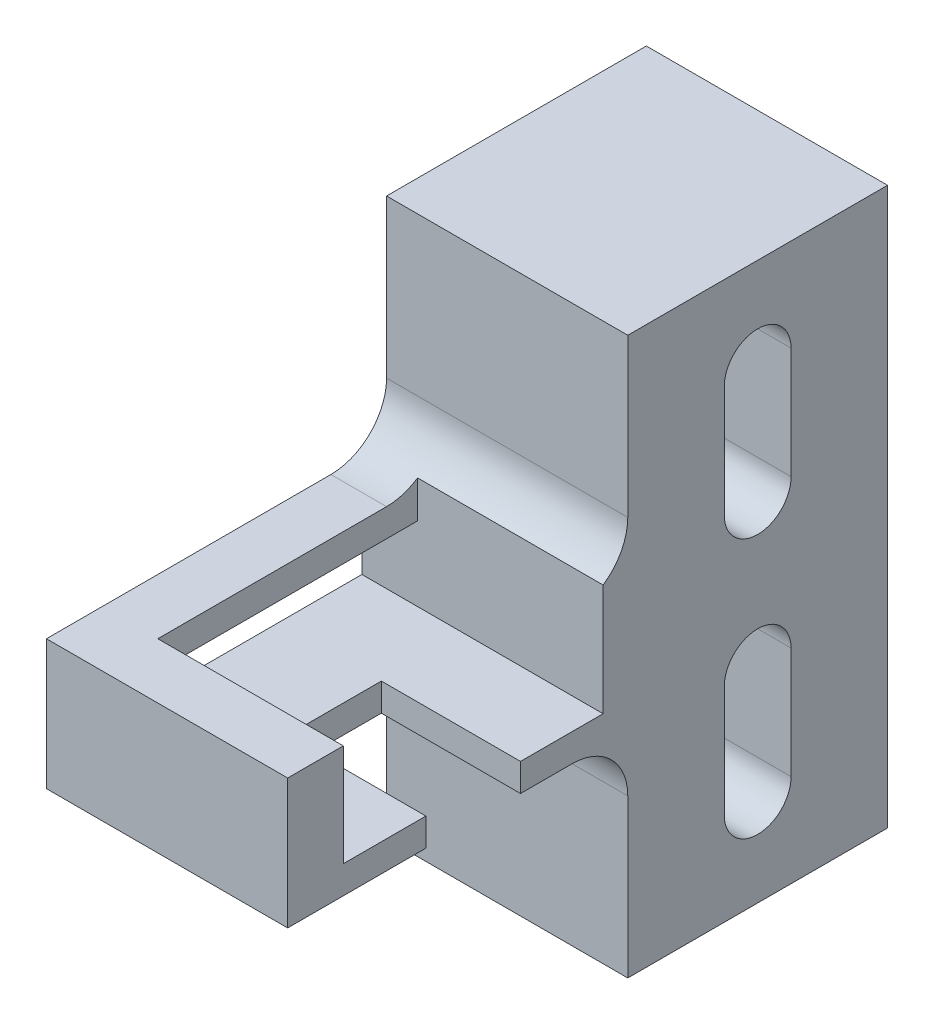
SolidWorks part; units mm, degrees
ref_plane "Front Plane" through (0, 0, 0) normal (0, 0, 1) x (1, 0, 0)
ref_plane "Top Plane" through (0, 0, 0) normal (0, 1, 0) x (1, 0, 0)
ref_plane "Right Plane" through (0, 0, 0) normal (1, 0, 0) x (0, 0, -1)
sketch "Sketch1" plane through (0, 0, 0) normal (0, 0, 1) x (1, 0, 0)
  line L0 (6.5, 30) -> (6.5, 25.2) construction
  line L1 (0, 0) -> (13, 0)
  line L2 (0, 0) -> (0, 30)
  line L3 (0, 30) -> (13, 30)
  line L4 (13, 0) -> (13, 30)
  line L5 (6.5, 25.2) -> (6.5, 4.8) construction
  line L6 (6.5, 4.8) -> (6.5, 0) construction
  dimension "D1" = 30
  dimension "D2" = 13
extrude "Boss-Extrude1" add sketch "Sketch1" along normal blind 14
sketch "Sketch2" plane through (0, 0, 14) normal (0, 0, 1) x (1, 0, 0)
  line L0 (0, 30) -> (0, 0) construction
  line L1 (0, 11.5) -> (13, 11.5)
  line L2 (0, 11.5) -> (0, 18.5)
  line L3 (0, 18.5) -> (13, 18.5)
  line L4 (13, 11.5) -> (13, 18.5)
  line L5 (13, 0) -> (13, 30) construction
  point P8 (0, 15)
  point P9 (0, 15)
  dimension "D1" = 7
extrude "Boss-Extrude2" add sketch "Sketch2" along normal blind 18.33
sketch "Sketch3" plane through (0, 18.5, 0) normal (0, 1, 0) x (1, 0, 0)
  line L0 (13, -32.33) -> (13, -14) construction
  line L1 (13, -29.33) -> (3, -29.33)
  line L2 (13, -29.33) -> (13, -15.33)
  line L3 (13, -15.33) -> (3, -15.33)
  line L4 (3, -29.33) -> (3, -15.33)
  line L5 (13, -32.33) -> (0, -32.33) construction
  dimension "D1" = 14
  dimension "D2" = 10
  dimension "D3" = 3
extrude "Cut-Extrude1" cut sketch "Sketch3" against normal blind 5.5
sketch "Sketch4" plane through (3, 0, 0) normal (1, 0, 0) x (0, 0, -1)
  line L1 (-29.33, 13) -> (-15.33, 13)
  line L2 (-29.33, 13) -> (-29.33, 17)
  line L3 (-29.33, 17) -> (-15.33, 17)
  line L4 (-15.33, 13) -> (-29.33, 13) construction
  line L8 (-15.33, 13) -> (-15.33, 17)
  line L9 (-15.33, 13) -> (-15.33, 18.5) construction
  dimension "D1" = 4
extrude "Cut-Extrude2" cut sketch "Sketch4" against normal through all
fillet "Fillet1" radius 3 2 edges
sketch "Sketch5" plane through (0, 0, 0) normal (-1, 0, 0) x (0, 0, 1)
  line L0 (7, 30) -> (7, 22) construction
  line L1 (14, 30) -> (0, 30) construction
  line L2 (7, 22) -> (7, 8) construction
  line L3 (7, 8) -> (7, 0) construction
  line L4 (14, 0) -> (0, 0) construction
  line L5 (7, 5) -> (7, 11) construction
  line L6 (5.2, 5) -> (5.2, 11)
  line L7 (8.8, 5) -> (8.8, 11)
  line L8 (7, 19) -> (7, 25) construction
  line L9 (5.2, 19) -> (5.2, 25)
  line L10 (8.8, 19) -> (8.8, 25)
  arc A0 (5.2, 5) -> (8.8, 5) centre (7, 5) ccw
  arc A1 (8.8, 11) -> (5.2, 11) centre (7, 11) ccw
  arc A2 (5.2, 19) -> (8.8, 19) centre (7, 19) ccw
  arc A3 (8.8, 25) -> (5.2, 25) centre (7, 25) ccw
  point P10 (7, 8)
  point P16 (7, 22)
  dimension "D1" = 1.8
  dimension "D2" = 8
  dimension "D3" = 6
  dimension "D4" = 3.2
  dimension "D5" = 14
extrude "Cut-Extrude3" cut sketch "Sketch5" against normal through all
sketch "Sketch6" plane through (0, 13, 0) normal (0, 1, 0) x (1, 0, 0)
  line L0 (13, -29.33) -> (13, -15.33) construction
  line L1 (13, -19.78) -> (5.5, -19.78)
  line L2 (13, -19.78) -> (13, -24.88)
  line L3 (13, -24.88) -> (5.5, -24.88)
  line L4 (5.5, -19.78) -> (5.5, -24.88)
  point P6 (13, -22.33)
  point P7 (13, -22.33)
  dimension "D1" = 7.5
  dimension "D2" = 5.1
extrude "Cut-Extrude4" cut sketch "Sketch6" against normal through all
